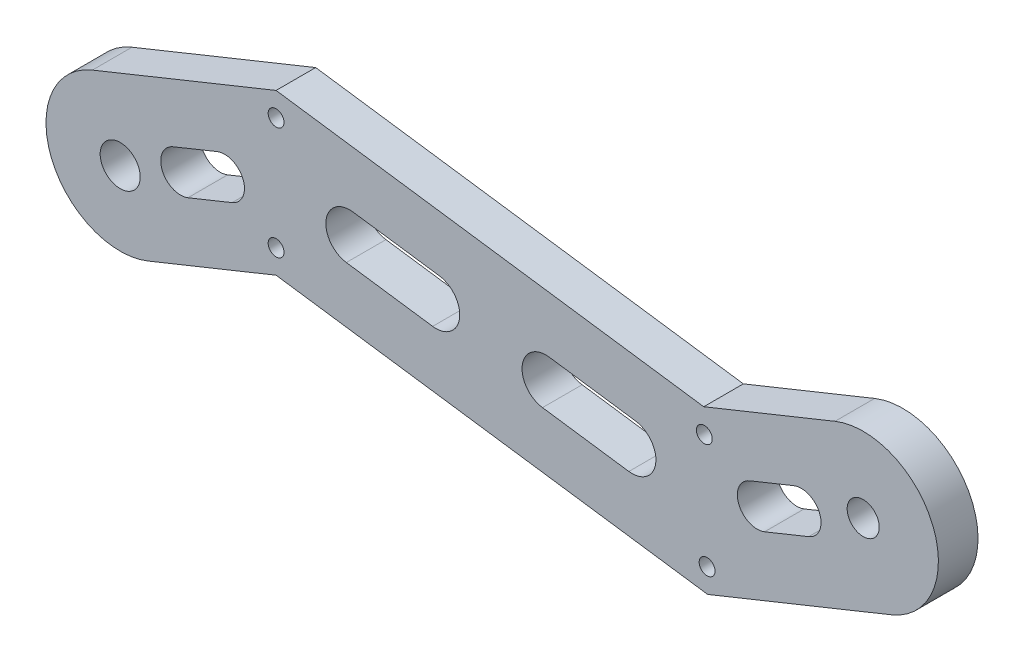
SolidWorks part; units mm, degrees
ref_plane "Front Plane" through (0, 0, 0) normal (0, 0, 1) x (1, 0, 0)
ref_plane "Top Plane" through (0, 0, 0) normal (0, 1, 0) x (1, 0, 0)
ref_plane "Right Plane" through (0, 0, 0) normal (1, 0, 0) x (0, 0, -1)
sketch "Sketch2" plane through (0, 0, 0) normal (0, 0, 1) x (1, 0, 0)
  line L0 (-52.5256, 39.0736) -> (55.4083, 23.9045)
  line L1 (-52.5256, -1.3195) -> (56.4039, -16.6285)
  line L2 (55.4083, 23.9045) -> (88.5451, 37.2926)
  line L3 (56.4039, -16.6285) -> (102.7631, 2.1018)
  line L4 (-52.5256, 39.0736) -> (-98.8848, 20.3433)
  line L5 (-52.5256, -1.3195) -> (-84.8551, -14.3815)
  line L6 (-52.5256, 39.0736) -> (-52.5256, -1.3195) construction
  line L7 (55.4083, 23.9045) -> (56.4039, -16.6285) construction
  line L8 (-91.8699, 2.9809) -> (-52.5256, 18.8771) construction
  line L9 (-52.5256, 18.8771) -> (55.9061, 3.638) construction
  line L10 (55.9061, 3.638) -> (95.6541, 19.6972) construction
  line L11 (-33.9594, 16.2678) -> (-12.1735, 13.2059) construction
  line L12 (-122.2976, 38.9357) -> (124.4009, 38.9357) construction
  line L13 (-122.2976, 38.9357) -> (-122.2976, -26.3788) construction
  line L14 (-122.2976, -26.3788) -> (124.4009, -26.3788) construction
  line L15 (124.4009, 38.9357) -> (124.4009, -26.3788) construction
  line L16 (-33.1244, 22.2094) -> (-11.3385, 19.1476)
  line L17 (-34.7944, 10.3261) -> (-13.0085, 7.2643)
  line L18 (-76.6324, 9.1373) -> (-65.5062, 13.6326) construction
  line L19 (-78.5054, 13.7732) -> (-67.3792, 18.2685)
  line L20 (-74.7593, 4.5014) -> (-63.6331, 8.9967)
  line L21 (68.8867, 8.8825) -> (80.0129, 13.3778) construction
  line L22 (67.0136, 13.5184) -> (78.1399, 18.0137)
  line L23 (70.7597, 4.2466) -> (81.8859, 8.7418)
  line L24 (15.554, 9.3091) -> (37.3399, 6.2473) construction
  line L25 (16.389, 15.2507) -> (38.1749, 12.1889)
  line L26 (14.719, 3.3675) -> (36.5049, 0.3057)
  line L27 (1.6903, 11.2575) -> (2.7609, 18.8756) construction
  arc A0 (88.5451, 37.2926) -> (102.7631, 2.1018) centre (95.6541, 19.6972) cw
  arc A1 (-98.8848, 20.3433) -> (-84.8551, -14.3815) centre (-91.8699, 2.9809) ccw
  circle A2 centre (-91.8699, 2.9809) radius 5.05
  circle A3 centre (95.6541, 19.6972) radius 4.05
  circle A4 centre (-52.5256, 33.0736) radius 2
  circle A5 centre (55.5557, 17.9045) radius 2
  arc A6 (-78.5054, 13.7732) -> (-74.7593, 4.5014) centre (-76.6324, 9.1373) ccw
  arc A7 (-63.6331, 8.9967) -> (-67.3792, 18.2685) centre (-65.5062, 13.6326) ccw
  arc A8 (67.0136, 13.5184) -> (70.7597, 4.2466) centre (68.8867, 8.8825) ccw
  arc A9 (81.8859, 8.7418) -> (78.1399, 18.0137) centre (80.0129, 13.3778) ccw
  circle A10 centre (-52.5256, 4.6805) radius 2
  circle A11 centre (56.2565, -10.6285) radius 2
  arc A12 (-33.1244, 22.2094) -> (-34.7944, 10.3261) centre (-33.9594, 16.2678) ccw
  arc A13 (-13.0085, 7.2643) -> (-11.3385, 19.1476) centre (-12.1735, 13.2059) ccw
  arc A14 (16.389, 15.2507) -> (14.719, 3.3675) centre (15.554, 9.3091) ccw
  arc A15 (36.5049, 0.3057) -> (38.1749, 12.1889) centre (37.3399, 6.2473) ccw
  point P27 (-71.0693, 11.3849)
  point P34 (74.4498, 11.1301)
  point P42 (-23.0665, 14.7368)
  point P47 (26.447, 7.7782)
  dimension "D15" = 10.1
  dimension "D16" = 8.1
  dimension "D7" = 4
  dimension "D17" = 4
  dimension "D22" = 4
  dimension "D23" = 4
  dimension "D1" = 150
  dimension "D2" = 110
  dimension "D3" = 50
  dimension "D4" = 8
  dimension "D5" = 150
  dimension "D6" = 12
  dimension "D8" = 20
  dimension "D9" = 12
  dimension "D10" = 20
  dimension "D11" = 50
  dimension "D12" = 20
  dimension "D13" = 10
  dimension "D14" = 10
  dimension "D18" = 6
  dimension "D19" = 6
  dimension "D20" = 6
  dimension "D21" = 6
  dimension "D24" = 25
  dimension "D25" = 22
  dimension "D26" = 25
  dimension "D27" = 22
  dimension "D28" = 12
  dimension "D29" = 12
extrude "Boss-Extrude1" add sketch "Sketch2" along normal blind 10
